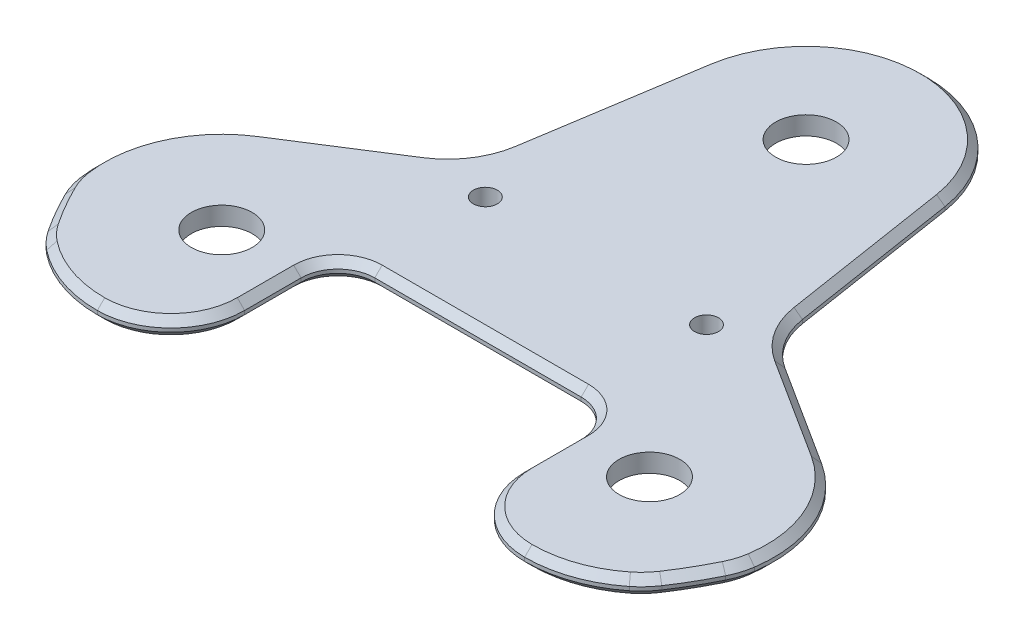
SolidWorks part; units mm, degrees
ref_plane "Front Plane" through (0, 0, 0) normal (0, 0, 1) x (1, 0, 0)
ref_plane "Top Plane" through (0, 0, 0) normal (0, 1, 0) x (1, 0, 0)
ref_plane "Right Plane" through (0, 0, 0) normal (1, 0, 0) x (0, 0, -1)
sketch "Sketch1" plane through (0, 0, 0) normal (0, 1, 0) x (1, 0, 0)
  line L0 (-19, -46.2493) -> (-19, -11)
  line L1 (-19, -11) -> (19, -11)
  line L2 (19, -11) -> (19, -46.2493)
  line L3 (0, 0) -> (0, 54.0669) construction
  circle A0 centre (0, 0) radius 50
  circle A1 centre (-15, 5) radius 1.625
  circle A2 centre (15, 5) radius 1.625
  point P13 (0, -11)
  dimension "D1" = 100
  dimension "D6" = 3.25
  dimension "D2" = 5
  dimension "D3" = 15
  dimension "D4" = 11
  dimension "D5" = 38
extrude "Boss-Extrude1" add sketch "Sketch1" along normal blind 2.5
fillet "Fillet1" radius 5 4 edges at (19, 1.25, 46.2493) (-19, 1.25, 46.2493) (19, 1.25, 11) (-19, 1.25, 11)
sketch "Sketch2" [suppressed] plane through (0, 5, 0) normal (0, 1, 0) x (1, 0, 0)
  line L0 (0, 0) -> (0, 28.9616) construction
  line L1 (0, 0) -> (-25.0815, -14.4808) construction
  circle A0 centre (0, 28.9616) radius 2.5
  circle A1 centre (-25.0815, -14.4808) radius 2.5
  circle A2 centre (25.0815, -14.4808) radius 2.5
  dimension "D3" = 5.5
extrude "Cut-Extrude1" [suppressed] cut sketch "Sketch2" against normal through all
sketch "Sketch3" plane through (0, 2.5, 0) normal (0, 1, 0) x (1, 0, 0)
  line L0 (0, 0) -> (-8.3914, 40.8434) construction
  line L1 (0, 0) -> (0, 33.5) construction
  circle A0 centre (0, 33.5) radius 4.125
  circle A1 centre (29.0119, -16.75) radius 4.125
  circle A2 centre (-29.0119, -16.75) radius 4.125
  point P12 (0, 0)
  dimension "D4" = 8.25
  dimension "D1" = 11.61
  dimension "D3" = 33.5
  dimension "D2" = 3
extrude "Cut-Extrude2" cut sketch "Sketch3" against normal through all
sketch "Sketch4" plane through (0, 2.5, 0) normal (0, 1, 0) x (1, 0, 0)
  line L1 (0, -1.375) -> (0, 1.375) construction
  line L2 (-29.0119, -33.6535) -> (29.0119, -33.6535)
  line L3 (2.2896, 63.5435) -> (90.3874, 30.8057)
  line L4 (90.3874, 30.8057) -> (57.0978, -64.8328)
  line L5 (57.0978, -64.8328) -> (-59.1397, -62.6258)
  line L6 (-59.1397, -62.6258) -> (-85.6242, 25.8398)
  line L7 (-85.6242, 25.8398) -> (2.2896, 63.5435)
  line L8 (-16.3013, 36.0531) -> (-21.0172, 5.9424)
  line L9 (-18.273, 10.1364) -> (-38.0955, -2.4946)
  line L10 (18.273, 10.1364) -> (38.0955, -2.4946)
  line L11 (16.3013, 36.0531) -> (21.0172, 5.9424)
  circle A0 centre (0, 33.5) radius 16.5
  circle A1 centre (29.0119, -16.75) radius 16.9035
  circle A2 centre (-29.0119, -16.75) radius 16.9035
  circle A3 centre (-15, 5) radius 6.0906
  circle A4 centre (15, 5) radius 6.0906
extrude "Cut-Extrude3" cut sketch "Sketch4" against normal through all
fillet "Fillet2" radius 10 8 edges at (-40.8868, 1.25, 28.7797) (-45.3673, 1.25, 21.0192) (40.8868, 1.25, 28.7797) (45.3673, 1.25, 21.0192) (20.5918, 1.25, -8.6589) (-20.5918, 1.25, -8.6589) (-19, 1.25, 30.3695) (19, 1.25, 30.3695)
chamfer "Chamfer1" distance 1 angle 45 48 edges at (17.5355, 0, 12.4645) (19, 0, 19.8267) (0, 0, 11) (21.9229, 0, 30.7185) (-17.5355, 0, 12.4645) (34.559, 0, 32.7174) (-19, 0, 19.8267) (40.6606, 0, 28.9297) (-21.9229, 0, 30.7185) (43.3013, 0, 25) (-34.559, 0, 32.7174) (45.3841, 0, 20.7482) (-40.6606, 0, 28.9297) (44.3884, 0, 9.7294) (-43.3013, 0, 25) (31.2472, 0, -1.8691) (-45.3841, 0, 20.7482) (21.405, 0, -9.1909) (-44.3884, 0, 9.7294) (18.0973, 0, -24.586) (-31.2472, 0, -1.8691) (0, 0, -50) (-21.405, 0, -9.1909) (-18.0973, 0, -24.586) (19, 2.5, 19.8267) (21.9229, 2.5, 30.7185) (17.5355, 2.5, 12.4645) (34.559, 2.5, 32.7174) (0, 2.5, 11) (40.6606, 2.5, 28.9297) (-17.5355, 2.5, 12.4645) (43.3013, 2.5, 25) (-19, 2.5, 19.8267) (45.3841, 2.5, 20.7482) (-21.9229, 2.5, 30.7185) (44.3884, 2.5, 9.7294) (-34.559, 2.5, 32.7174) (31.2472, 2.5, -1.8691) (-40.6606, 2.5, 28.9297) (21.405, 2.5, -9.1909) (-43.3013, 2.5, 25) (18.0973, 2.5, -24.586) (-45.3841, 2.5, 20.7482) (0, 2.5, -50) (-44.3884, 2.5, 9.7294) (-18.0973, 2.5, -24.586) (-31.2472, 2.5, -1.8691) (-21.405, 2.5, -9.1909)
equation "\"mounting hole\"= 5.5mm"
equation "\"servo holes\"= 4.5mm"
equation "\"mounting hole dist from center\"= 25mm"
equation "\"D3@Sketch2\"=\"mounting hole\""
equation "\"mounting sketch rotation\"= 11.60507646deg"
equation "\"D1@Sketch3\"=\"mounting sketch rotation\""
equation "\"D4@Sketch3\"=\"mounting hole\"*1.5"
